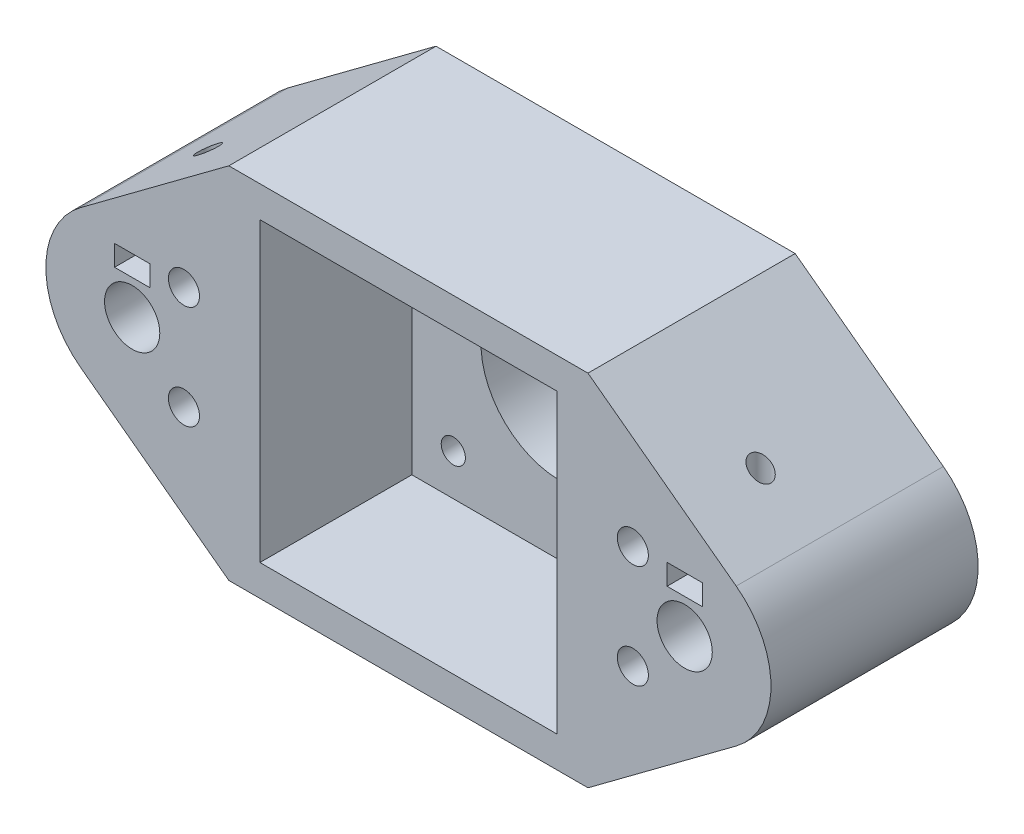
SolidWorks part; units mm, degrees
material "ABS"
ref_plane "Plano frontal" through (0, 0, 0) normal (0, 0, 1) x (1, 0, 0)
ref_plane "Plano superior" through (0, 0, 0) normal (0, 1, 0) x (1, 0, 0)
ref_plane "Plano direito" through (0, 0, 0) normal (1, 0, 0) x (0, 0, -1)
sketch "Esboço1" plane through (0, 0, 0) normal (0, 0, 1) x (1, 0, 0)
  line L0 (-40, 0) -> (40, 0) construction
  line L1 (-15.5, -15.5) -> (15.5, -15.5) construction
  line L2 (-15.5, -15.5) -> (-15.5, 15.5) construction
  line L3 (-15.5, 15.5) -> (15.5, 15.5) construction
  line L4 (15.5, -15.5) -> (15.5, 15.5) construction
  line L5 (-15.5, -15.5) -> (15.5, 15.5) construction
  line L6 (-15.5, 15.5) -> (15.5, -15.5) construction
  line L7 (-26, 26) -> (26, 26)
  line L9 (-26, -26) -> (26, -26)
  line L11 (-26, 26) -> (26, -26) construction
  line L12 (-26, -26) -> (26, 26) construction
  line L13 (-26, 26) -> (-47.4626, 10.0279)
  line L14 (-26, -26) -> (-47.4626, -10.0279)
  line L15 (0, 33.9492) -> (0, -26.7365) construction
  line L16 (26, 26) -> (47.4626, 10.0279)
  line L18 (47.4626, -10.0279) -> (26, -26)
  circle A0 centre (-15.5, 15.5) radius 1.75
  circle A1 centre (15.5, 15.5) radius 1.75
  circle A2 centre (15.5, -15.5) radius 1.75
  circle A3 centre (-15.5, -15.5) radius 1.75
  circle A4 centre (0, 0) radius 11.5
  circle A5 centre (-40, 0) radius 4
  circle A6 centre (40, 0) radius 4
  arc A7 (-47.4626, 10.0279) -> (-47.4626, -10.0279) centre (-40, 0) ccw
  arc A8 (47.4626, -10.0279) -> (47.4626, 10.0279) centre (40, 0) ccw
  circle A9 centre (-32.5, 7.5) radius 2.25
  circle A10 centre (-32.5, -7.5) radius 2.25
  circle A11 centre (32.5, -7.5) radius 2.25
  circle A12 centre (32.5, 7.5) radius 2.25
  point P0 (0, 0)
  point P10 (0, 0)
  point P21 (0, 0)
  point P39 (0, 26)
  dimension "D2" = 3.5
  dimension "D3" = 23
  dimension "D6" = 8
  dimension "D7" = 25
  dimension "D9" = 4.5
  dimension "D1" = 31
  dimension "D4" = 52
  dimension "D5" = 80
  dimension "D8" = 15
  dimension "D10" = 32.5
  dimension "D11" = 52
extrude "Ressalto-extrusão1" add sketch "Esboço1" along normal blind 30
sketch "Esboço2" plane through (0, 0, 30) normal (0, 0, 1) x (1, 0, 0)
  line L0 (-40, 0) -> (-40, 19.2268) construction
  line L1 (-21.5, 21.5) -> (21.5, 21.5)
  line L2 (-21.5, 21.5) -> (-21.5, -21.5)
  line L3 (-21.5, -21.5) -> (21.5, -21.5)
  line L4 (21.5, 21.5) -> (21.5, -21.5)
  line L5 (-21.5, 21.5) -> (21.5, -21.5) construction
  line L6 (-21.5, -21.5) -> (21.5, 21.5) construction
  line L7 (0, 0) -> (0, 15.4775) construction
  line L8 (-42.55, 8) -> (-37.45, 8)
  line L9 (-42.55, 8) -> (-42.55, 5)
  line L10 (-42.55, 5) -> (-37.45, 5)
  line L11 (-37.45, 8) -> (-37.45, 5)
  line L12 (-42.55, 8) -> (-37.45, 5) construction
  line L13 (-42.55, 5) -> (-37.45, 8) construction
  line L14 (42.55, 5) -> (37.45, 8) construction
  line L15 (42.55, 8) -> (37.45, 5) construction
  line L16 (40, 0) -> (40, 19.2268) construction
  line L17 (37.45, 8) -> (37.45, 5)
  line L18 (42.55, 5) -> (37.45, 5)
  line L19 (42.55, 8) -> (42.55, 5)
  line L20 (42.55, 8) -> (37.45, 8)
  circle A0 centre (-40, 0) radius 4 construction
  point P0 (0, 0)
  point P9 (-40, 6.5)
  point P24 (40, 6.5)
  dimension "D1" = 43
  dimension "D2" = 5
  dimension "D3" = 3
  dimension "D4" = 5.1
extrude "Corte-extrusão1" cut sketch "Esboço2" against normal blind 22
sketch "Esboço3" plane through (0, 0, 0) normal (0, 0, -1) x (-1, 0, 0)
  circle A0 centre (-15.5, 15.5) radius 4.5
  circle A1 centre (15.5, 15.5) radius 4.5
  circle A2 centre (-15.5, -15.5) radius 4.5
  circle A3 centre (15.5, -15.5) radius 4.5
  dimension "D1" = 9
extrude "Corte-extrusão2" cut sketch "Esboço3" against normal blind 3
sketch "Esboço4" plane through (0, 5, 0) normal (0, 1, 0) x (1, 0, 0)
  line L0 (-37.45, -8) -> (-37.45, -30) construction
  line L1 (-42.55, -8) -> (-37.45, -8) construction
  line L2 (0, 0) -> (0, -35.8103) construction
  circle A0 centre (-40, -19) radius 1.5
  circle A1 centre (40, -19) radius 1.5
  point P4 (-37.45, -19)
  point P8 (-40, -8)
  dimension "D1" = 3
extrude "Corte-extrusão3" cut sketch "Esboço4" against normal blind 3 and the other way through all
equation "\"D11@Esboço1\"=\"D4@Esboço1\""
